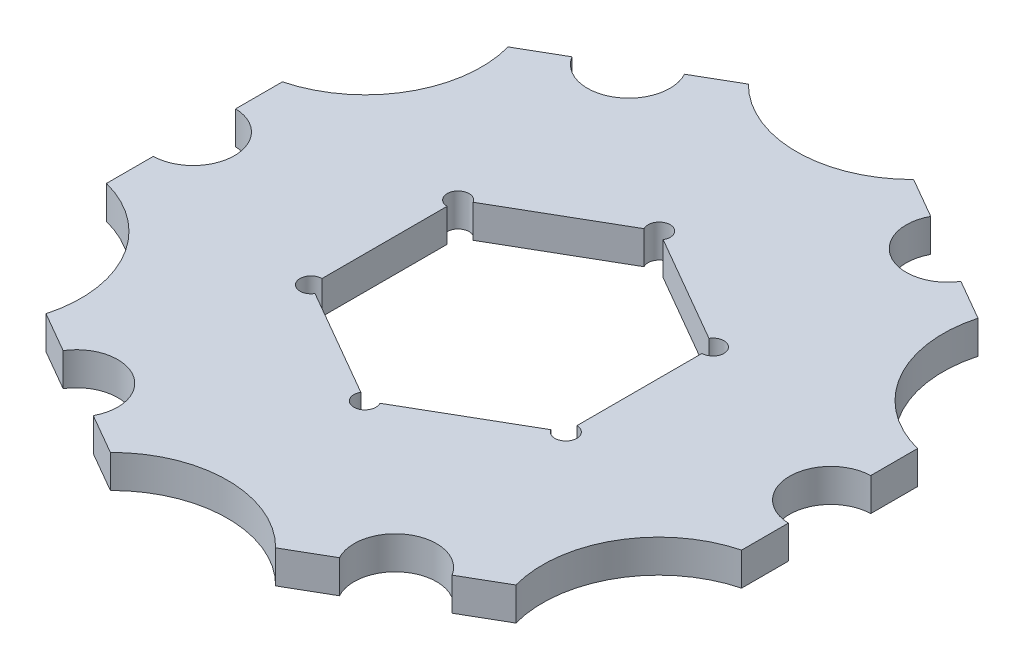
SolidWorks part; units mm, degrees
material "7075-T6 (SN)"
ref_plane "Front Plane" through (0, 0, 0) normal (0, 0, 1) x (1, 0, 0)
ref_plane "Top Plane" through (0, 0, 0) normal (0, 1, 0) x (1, 0, 0)
ref_plane "Right Plane" through (0, 0, 0) normal (1, 0, 0) x (0, 0, -1)
sketch "Sketch1" plane through (0, 0, 0) normal (0, 1, 0) x (1, 0, 0)
  line L0 (0, 0) -> (-62.5623, 0) construction
  line L1 (18.4023, 10.6246) -> (0, 21.2491)
  line L2 (0, 21.2491) -> (-18.4023, 10.6246)
  line L3 (-18.4023, 10.6246) -> (-18.4023, -10.6246)
  line L4 (-18.4023, -10.6246) -> (0, -21.2491)
  line L5 (0, -21.2491) -> (18.4023, -10.6246)
  line L6 (18.4023, -10.6246) -> (18.4023, 10.6246)
  line L7 (-45.8597, 12.7) -> (-45.8597, 5.9505)
  line L8 (-46.0375, 0) -> (-46.0375, -29.149) construction
  line L9 (-45.8597, -5.9505) -> (-45.8597, -12.7)
  line L10 (-28.0831, 36.7404) -> (-33.9284, 33.3657)
  line L11 (-11.9313, 46.0657) -> (-17.7766, 42.6909)
  line L12 (17.7766, 42.6909) -> (11.9313, 46.0657)
  line L13 (33.9284, 33.3657) -> (28.0831, 36.7404)
  line L14 (45.8597, 5.9505) -> (45.8597, 12.7)
  line L15 (45.8597, -12.7) -> (45.8597, -5.9505)
  line L16 (28.0831, -36.7404) -> (33.9284, -33.3657)
  line L17 (11.9313, -46.0657) -> (17.7766, -42.6909)
  line L18 (-17.7766, -42.6909) -> (-11.9313, -46.0657)
  line L19 (-33.9284, -33.3657) -> (-28.0831, -36.7404)
  circle A0 centre (0, 0) radius 18.4023 construction
  circle A1 centre (-18.4023, 10.6246) radius 1.5875
  arc A2 (-46.0375, 5.9531) -> (-46.0375, -5.9531) centre (-46.0375, 0) ccw construction
  circle A3 centre (0, 21.2491) radius 1.5875
  circle A4 centre (18.4023, 10.6246) radius 1.5875
  circle A5 centre (18.4023, -10.6246) radius 1.5875
  circle A6 centre (0, -21.2491) radius 1.5875
  circle A7 centre (-18.4023, -10.6246) radius 1.5875
  arc A8 (-45.8597, 5.9505) -> (-45.8597, -5.9505) centre (-46.0375, 0) cw
  arc A9 (-45.8597, -5.9505) -> (-45.8597, 5.9505) centre (-46.0375, 0) ccw construction
  arc A10 (-17.7766, 42.6909) -> (-28.0831, 36.7404) centre (-23.0188, 39.8696) cw
  arc A11 (28.0831, 36.7404) -> (17.7766, 42.6909) centre (23.0187, 39.8696) cw
  arc A12 (45.8597, -5.9505) -> (45.8597, 5.9505) centre (46.0375, 0) cw
  arc A13 (17.7766, -42.6909) -> (28.0831, -36.7404) centre (23.0188, -39.8696) cw
  arc A14 (-28.0831, -36.7404) -> (-17.7766, -42.6909) centre (-23.0188, -39.8696) cw
  arc A15 (-45.8597, -12.7) -> (-33.9284, -33.3657) centre (-50.0924, -28.9209) cw
  arc A16 (-33.9284, 33.3657) -> (-45.8597, 12.7) centre (-50.0924, 28.9209) cw
  arc A17 (11.9313, 46.0657) -> (-11.9313, 46.0657) centre (0, 57.8417) cw
  arc A18 (45.8597, 12.7) -> (33.9284, 33.3657) centre (50.0924, 28.9209) cw
  arc A19 (33.9284, -33.3657) -> (45.8597, -12.7) centre (50.0924, -28.9209) cw
  arc A20 (-11.9313, -46.0657) -> (11.9313, -46.0657) centre (0, -57.8417) cw
  point P27 (0, 0)
  point P58 (0, 0)
  point P74 (0, 0)
  dimension "D1" = 11.9062
  dimension "D4" = 3.175
  dimension "D10" = 16.764
  dimension "D2" = 46.0375
  dimension "D3" = 36.8046
  dimension "D6" = 0.3556
  dimension "D7" = 25.4
  dimension "D5" = 6
  dimension "D8" = 6
  dimension "D9" = 6
extrude "Boss-Extrude1" add sketch "Sketch1" along normal blind 4.7625 contours L18 A20 L17 A13 L16 A19 L15 A12 L14 A18 L13 A11 L12 A17 L11 A10 L10 A16 L7 A8 L9 A15 L19 A14 A7 L3 A1 L2 A3 L1 A4 L6 A5 L5 A6 L4
